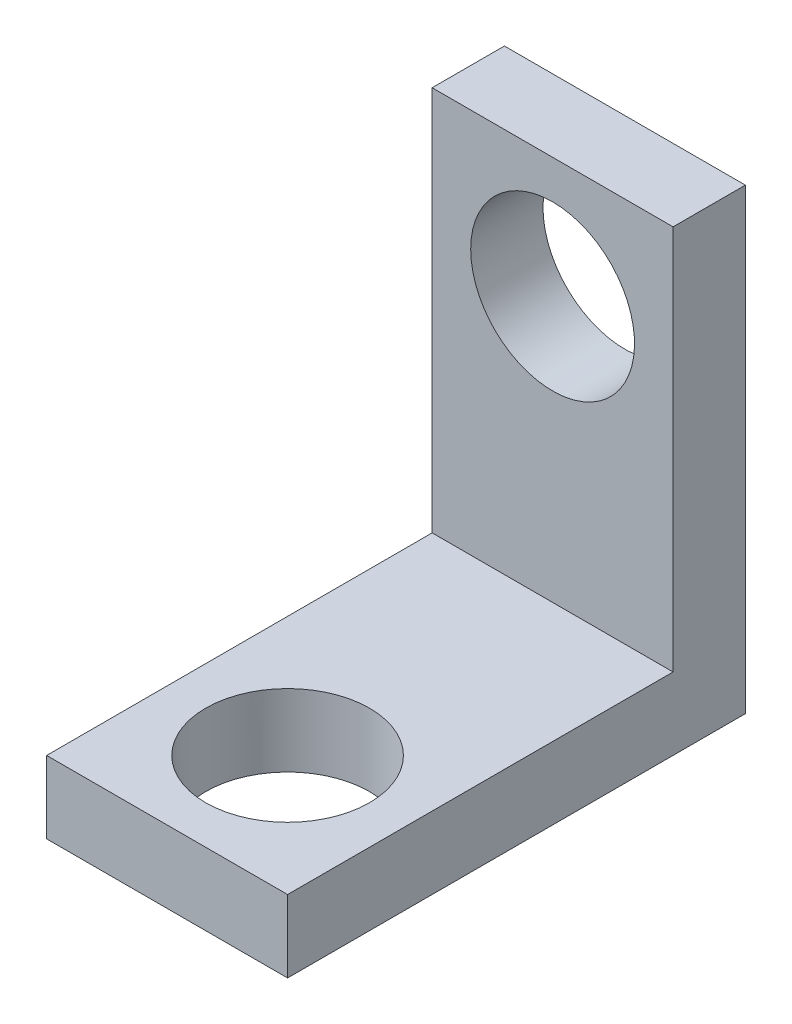
SolidWorks part; units mm, degrees
ref_plane "Front Plane" through (0, 0, 0) normal (0, 0, 1) x (1, 0, 0)
ref_plane "Top Plane" through (0, 0, 0) normal (0, 1, 0) x (1, 0, 0)
ref_plane "Right Plane" through (0, 0, 0) normal (1, 0, 0) x (0, 0, -1)
sketch "Sketch1" plane through (0, 0, 0) normal (1, 0, 0) x (0, 0, -1)
  line L1 (-4.75, -4.75) -> (4.75, -4.75)
  line L2 (-4.75, -4.75) -> (-4.75, 4.75)
  line L3 (-4.75, 4.75) -> (4.75, 4.75)
  line L4 (4.75, -4.75) -> (4.75, 4.75)
  line L5 (0, 4.75) -> (0, -4.75) construction
  line L6 (-4.75, 0) -> (4.75, 0) construction
  line L7 (-4.75, 4.75) -> (3.25, 4.75)
  line L8 (-4.75, 4.75) -> (-4.75, -3.25)
  line L9 (-4.75, -3.25) -> (3.25, -3.25)
  line L10 (3.25, 4.75) -> (3.25, -3.25)
  point P0 (0, 0)
  dimension "D1" = 9.5
  dimension "D2" = 9.5
  dimension "D3" = 1.5
  dimension "D4" = 1.5
extrude "Boss-Extrude1" add sketch "Sketch1" along normal blind 5 contours L3 L10 L9 L2 L1 L4
sketch "Sketch2" plane through (0, 0, -4.75) normal (0, 0, -1) x (-1, 0, 0)
  line L0 (-2.5, 4.75) -> (-2.5, -4.75) construction
  line L1 (-5, 4.75) -> (0, 4.75) construction
  line L2 (-5, -4.75) -> (0, -4.75) construction
  circle A0 centre (-2.5, 2.25) radius 1.7
  dimension "D1" = 3.4
  dimension "D2" = 7
extrude "Cut-Extrude1" cut sketch "Sketch2" against normal through all
sketch "Sketch3" plane through (0, -4.75, 0) normal (0, -1, 0) x (1, 0, 0)
  line L0 (2.5, 4.75) -> (2.5, -4.75) construction
  line L1 (5, 4.75) -> (0, 4.75) construction
  line L2 (5, -4.75) -> (0, -4.75) construction
  circle A0 centre (2.5, 2.25) radius 1.7
  dimension "D1" = 3.4
  dimension "D2" = 7
extrude "Cut-Extrude2" cut sketch "Sketch3" against normal through all
